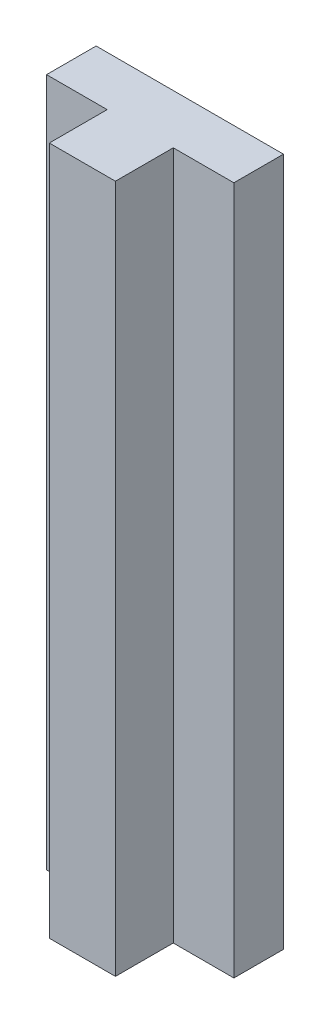
SolidWorks part; units mm, degrees
ref_plane "Alzado" through (0, 0, 0) normal (0, 0, 1) x (1, 0, 0)
ref_plane "Planta" through (0, 0, 0) normal (0, 1, 0) x (1, 0, 0)
ref_plane "Vista lateral" through (0, 0, 0) normal (1, 0, 0) x (0, 0, -1)
sketch "Croquis1" plane through (0, 0, 0) normal (0, 1, 0) x (1, 0, 0)
  line L0 (-18.451, 0) -> (18.451, 0) construction
  line L1 (0, 14.6078) -> (0, -14.6078) construction
  line L2 (-2.6, 0) -> (-2.6, 4) construction
  line L3 (-2.6, 4) -> (-7, 4) construction
  line L4 (-7, 4) -> (-7, 8) construction
  line L5 (-7, 8) -> (0, 8) construction
  line L6 (-2.4, 0) -> (-2.4, 4.2)
  line L7 (-2.4, 4.2) -> (-6.8, 4.2)
  line L8 (-6.8, 4.2) -> (-6.8, 7.8)
  line L9 (-6.8, 7.8) -> (0, 7.8)
  line L10 (-2.4, 0) -> (2.4, 0)
  line L11 (6.8, 7.8) -> (0, 7.8)
  line L12 (6.8, 4.2) -> (6.8, 7.8)
  line L13 (2.4, 4.2) -> (6.8, 4.2)
  line L14 (2.4, 0) -> (2.4, 4.2)
  point P6 (0, 0)
  point P17 (0, 0)
  dimension "D1" = 7
  dimension "D2" = 4
  dimension "D3" = 4
  dimension "D4" = 4.4
  dimension "D5" = 0.2
extrude "Saliente-Extruir1" add sketch "Croquis1" along normal blind 50
